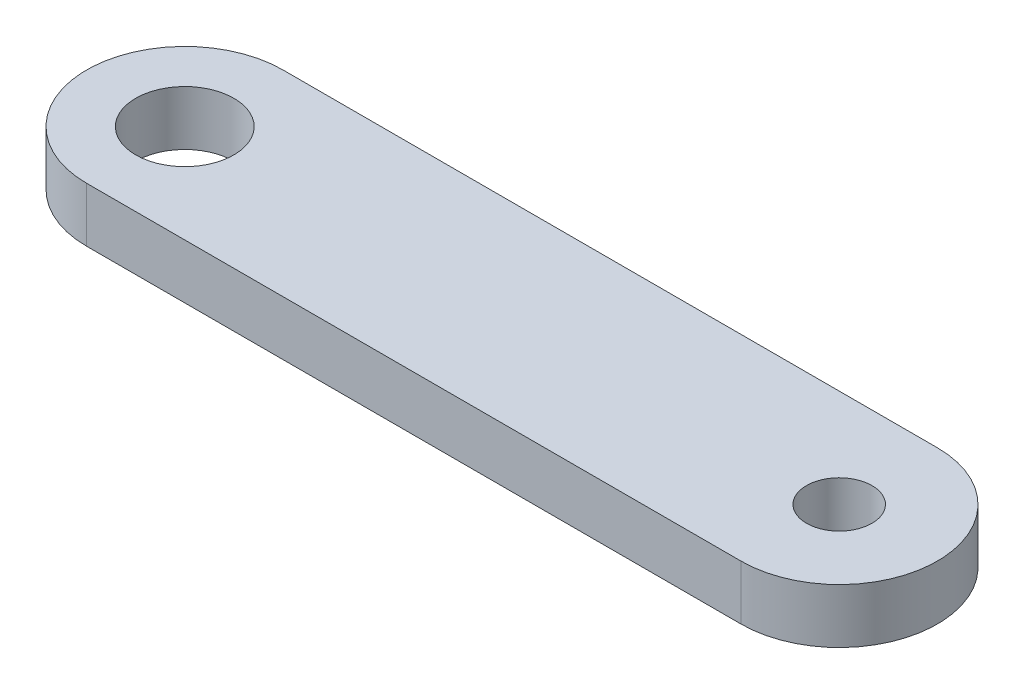
SolidWorks part; units mm, degrees
ref_plane "Front Plane" through (0, 0, 0) normal (0, 0, 1) x (1, 0, 0)
ref_plane "Top Plane" through (0, 0, 0) normal (0, 1, 0) x (1, 0, 0)
ref_plane "Right Plane" through (0, 0, 0) normal (1, 0, 0) x (0, 0, -1)
sketch "Sketch1" plane through (0, 0, 0) normal (0, 1, 0) x (1, 0, 0)
  line L0 (0, 0) -> (60, 0) construction
  line L1 (0, 9) -> (60, 9)
  line L2 (0, -9) -> (60, -9)
  circle A0 centre (0, 0) radius 4.5
  arc A1 (0, 9) -> (0, -9) centre (0, 0) ccw
  arc A2 (60, -9) -> (60, 9) centre (60, 0) ccw
  circle A3 centre (60, 0) radius 3
  point P4 (30, 0)
  dimension "D1" = 9
  dimension "D2" = 6
  dimension "D3" = 60
  dimension "D4" = 18
extrude "Boss-Extrude1" add sketch "Sketch1" along normal blind 5
